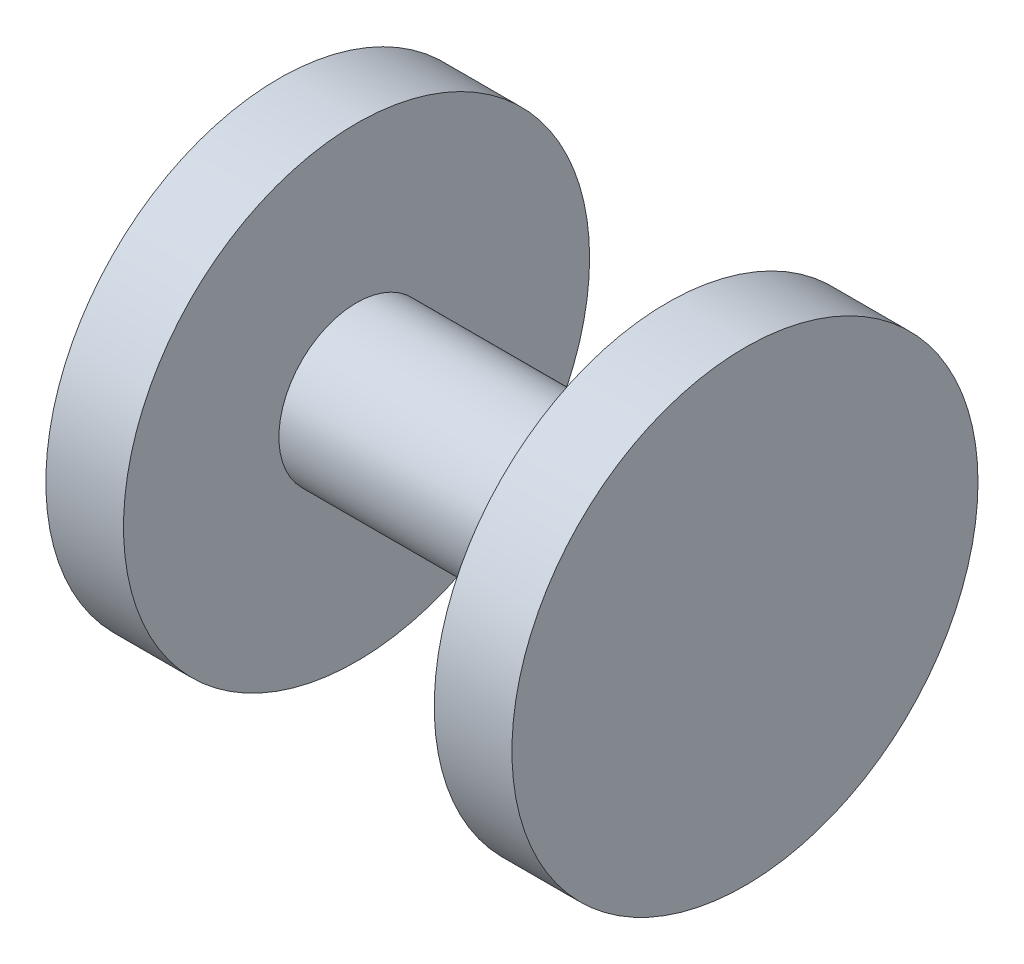
SolidWorks part; units mm, degrees
ref_plane "Alzado" through (0, 0, 0) normal (0, 0, 1) x (1, 0, 0)
ref_plane "Planta" through (0, 0, 0) normal (0, 1, 0) x (1, 0, 0)
ref_plane "Vista lateral" through (0, 0, 0) normal (1, 0, 0) x (0, 0, -1)
sketch "Croquis1" plane through (0, 0, 0) normal (0, 0, 1) x (1, 0, 0)
  line L0 (0, 0) -> (0, 15)
  line L1 (0, 15) -> (5, 15)
  line L2 (5, 15) -> (5, 5)
  line L3 (5, 5) -> (25, 5)
  line L4 (25, 5) -> (25, 15)
  line L5 (25, 15) -> (30, 15)
  line L6 (30, 15) -> (30, 0)
  line L7 (30, 0) -> (0, 0) construction
  line L8 (0, 0) -> (0.3599, 0.0777)
  line L9 (0, 0) -> (30, 0)
  dimension "D1" = 15
  dimension "D2" = 5
  dimension "D3" = 5
  dimension "D4" = 20
  dimension "D5" = 5
  dimension "D6" = 15
revolve "Revolución1" add sketch "Croquis1" angle 360 about L7
